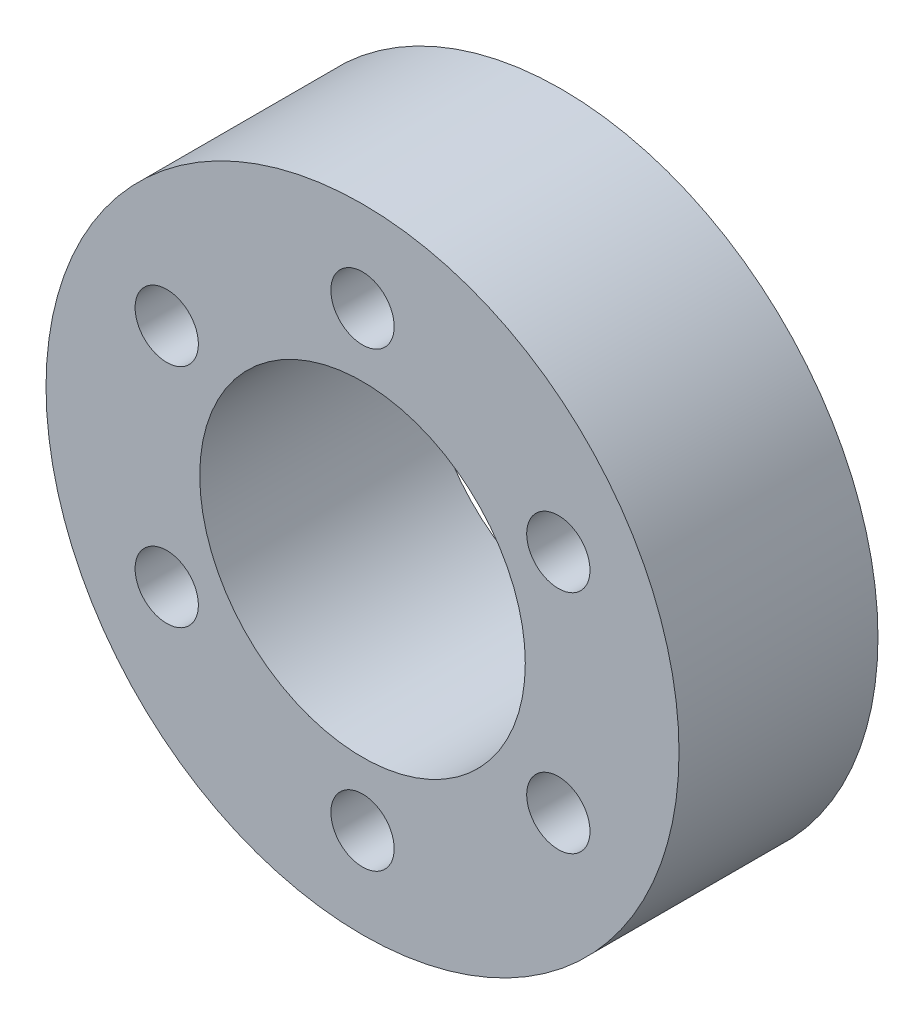
SolidWorks part; units mm, degrees
material "ABS"
ref_plane "前视基准面" through (0, 0, 0) normal (0, 0, 1) x (1, 0, 0)
ref_plane "上视基准面" through (0, 0, 0) normal (0, 1, 0) x (1, 0, 0)
ref_plane "右视基准面" through (0, 0, 0) normal (1, 0, 0) x (0, 0, -1)
sketch "草图1" plane through (0, 0, 0) normal (0, 0, 1) x (1, 0, 0)
  circle A0 centre (0, 0) radius 14.5
  dimension "D1" = 29
extrude "凸台-拉伸1" add sketch "草图1" along normal blind 1.5
sketch "草图2" plane through (0, 0, 1.5) normal (0, 0, 1) x (1, 0, 0)
  circle A0 centre (0, 0) radius 17.5
  dimension "D1" = 35
extrude "凸台-拉伸2" add sketch "草图2" along normal blind 11
sketch "草图3" plane through (0, 0, 0) normal (0, 0, -1) x (-1, 0, 0)
  circle A0 centre (0, 0) radius 12.5 construction
  circle A1 centre (0, 12.5) radius 1.75
  circle A7 centre (0, 0) radius 9
  circle A8 centre (10.8253, 6.25) radius 1.75
  circle A9 centre (10.8253, -6.25) radius 1.75
  circle A10 centre (0, -12.5) radius 1.75
  circle A11 centre (-10.8253, -6.25) radius 1.75
  circle A12 centre (-10.8253, 6.25) radius 1.75
  point P17 (0, 0)
  dimension "D1" = 25
  dimension "D2" = 3.5
  dimension "D4" = 18
  dimension "D3" = 6
extrude "切除-拉伸1" cut sketch "草图3" against normal blind 26.5
